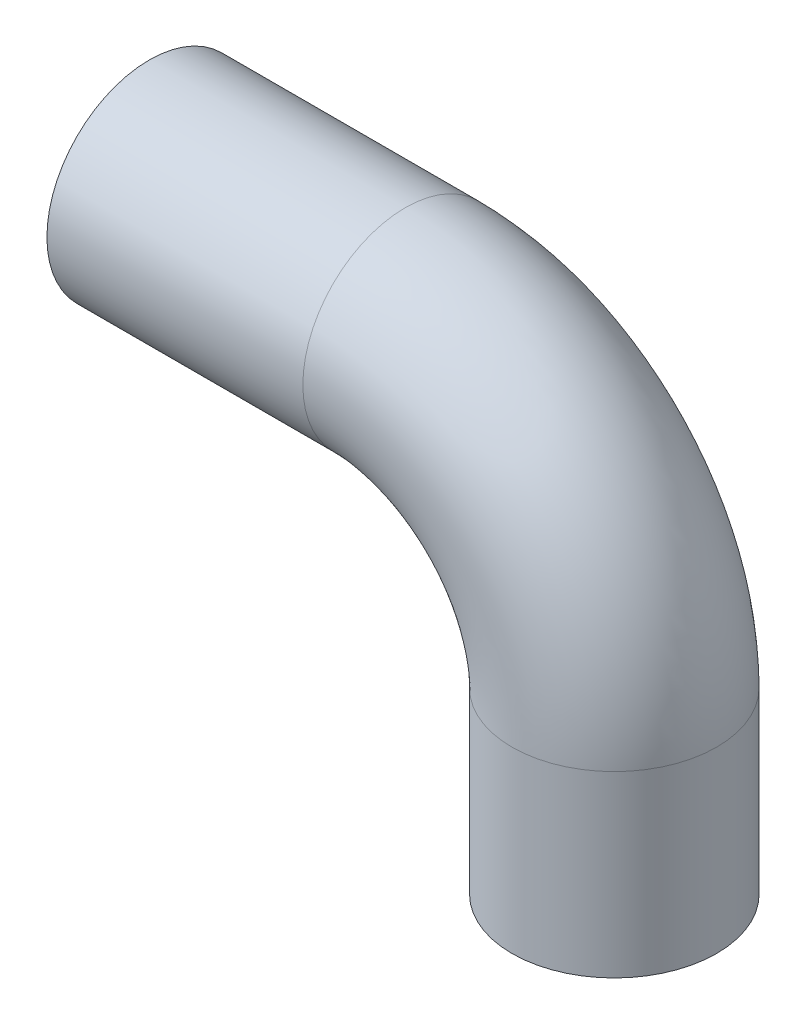
SolidWorks part; units mm, degrees
ref_plane "前视基准面" through (0, 0, 0) normal (0, 0, 1) x (1, 0, 0)
ref_plane "上视基准面" through (0, 0, 0) normal (0, 1, 0) x (1, 0, 0)
ref_plane "右视基准面" through (0, 0, 0) normal (1, 0, 0) x (0, 0, -1)
sketch "草图1" plane through (0, 0, 0) normal (0, 0, 1) x (1, 0, 0)
  line L0 (0, 0) -> (5, 0)
  line L1 (9.0849, -4.0849) -> (9.0849, -7.5765)
  arc A0 (5, 0) -> (9.0849, -4.0849) centre (5, -4.0849) cw
  dimension "D1" = 5
sketch "草图2" plane through (0, 0, 0) normal (1, 0, 0) x (0, 0, -1)
  circle A0 centre (0, 0) radius 1.25
  circle A1 centre (0, 0) radius 2
  dimension "D1" = 2.5
  dimension "D2" = 4
sweep "扫描1" add profiles "草图2" path "草图1"
